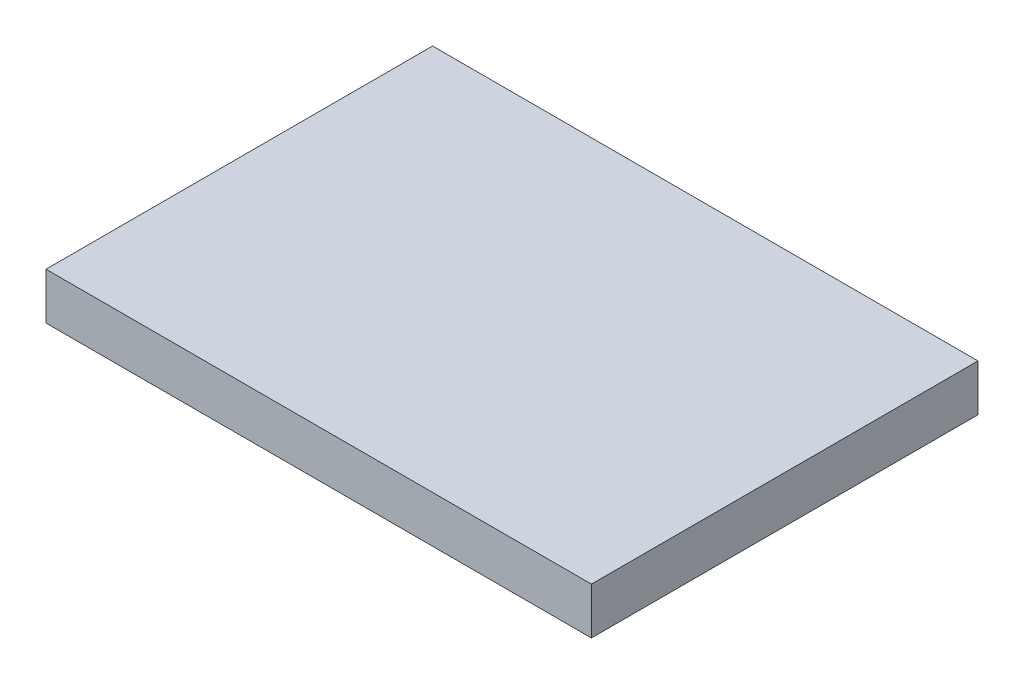
SolidWorks part; units mm, degrees
ref_plane "Front Plane" through (0, 0, 0) normal (0, 0, 1) x (1, 0, 0)
ref_plane "Top Plane" through (0, 0, 0) normal (0, 1, 0) x (1, 0, 0)
ref_plane "Right Plane" through (0, 0, 0) normal (1, 0, 0) x (0, 0, -1)
sketch "Sketch1" plane through (0, 0, 0) normal (1, 0, 0) x (0, 0, -1)
  line L1 (0, 0) -> (106.3148, 0)
  line L2 (0, 0) -> (0, 12.8277)
  line L3 (0, 12.8277) -> (106.3148, 12.8277)
  line L4 (106.3148, 0) -> (106.3148, 12.8277)
extrude "Extrude1" add sketch "Sketch1" along normal blind 150
